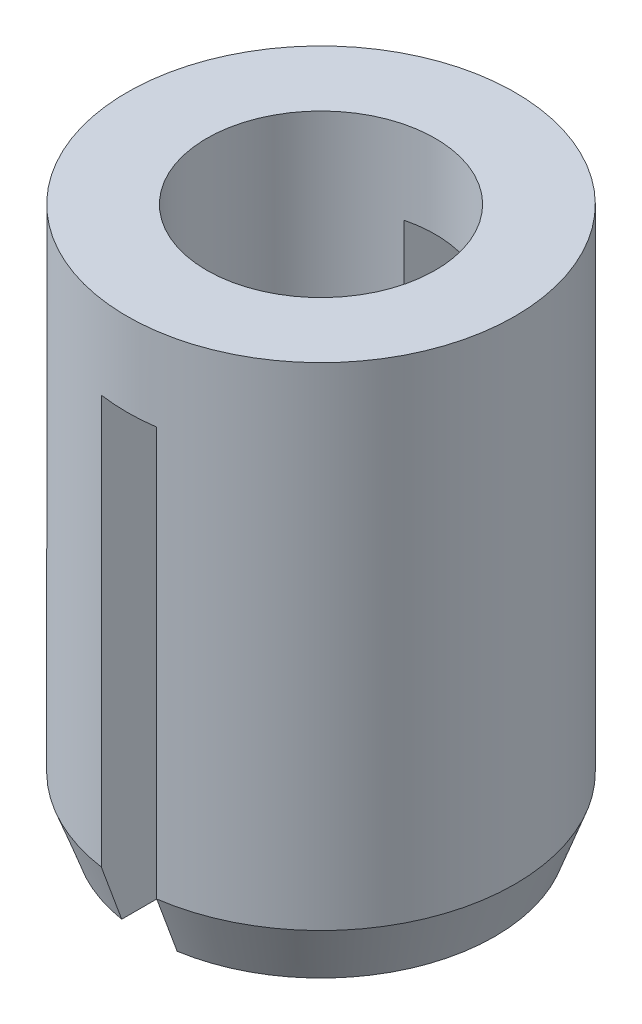
SolidWorks part; units mm, degrees
ref_plane "Front Plane" through (0, 0, 0) normal (0, 0, 1) x (1, 0, 0)
ref_plane "Top Plane" through (0, 0, 0) normal (0, 1, 0) x (1, 0, 0)
ref_plane "Right Plane" through (0, 0, 0) normal (1, 0, 0) x (0, 0, -1)
sketch "Sketch1" plane through (0, 0, 0) normal (0, 0, 1) x (1, 0, 0)
  line L0 (0, -7.9) -> (0, 0)
  line L1 (0, 0) -> (-2.8, 0)
  line L2 (-2.8, 0) -> (-2.8, -7.1)
  line L3 (-2.8, -7.1) -> (-2.5088, -7.9)
  line L4 (-2.5088, -7.9) -> (0, -7.9)
  line L5 (0, -7.9) -> (0, -6.7522) construction
  dimension "D1" = 7.9
  dimension "D2" = 5.6
  dimension "D3" = 0.8
  dimension "D4" = 20
revolve "Revolve1" add sketch "Sketch1" angle 360 about L5
hole_wizard "M4 Tapped Hole1" positions "Sketch3" profile "Sketch5" tap size "M4" standard "ISO" end condition through all
sketch "Sketch3" plane through (0, 0, 0) normal (0, 1, 0) x (1, 0, 0)
  point P0 (0, 0)
sketch "Sketch5" plane through (0, 0, 0) normal (1, 0, 0) x (0, 0, 1)
  line L0 (0, 0) -> (0, 7.9)
  line L1 (0, 7.9) -> (1.65, 7.9)
  line L2 (1.65, 7.9) -> (1.65, 0)
  line L5 (1.65, 0) -> (0, 0)
  line L11 (0, -6.35) -> (0, 107.95) construction
  dimension "Thru Tap Drill Dia." = 3.3
  dimension "Thru Tap Drill Depth" = 7.9
cosmetic thread "Hole Thread1" parameters "D2"=4
sketch "Sketch2" plane through (0, 0, 0) normal (0, 0, 1) x (1, 0, 0)
  line L0 (-1.65, -7.9) -> (1.65, -7.9) construction
  line L1 (0.4, -1.2) -> (-0.4, -1.2)
  line L2 (0.4, -1.2) -> (0.4, -7.9)
  line L3 (0.4, -7.9) -> (-0.4, -7.9)
  line L4 (-0.4, -1.2) -> (-0.4, -7.9)
  point P4 (0, -1.2)
  dimension "D1" = 0.8
  dimension "D2" = 1.2
extrude "Cut-Extrude1" cut sketch "Sketch2" against normal through all both and the other way through all
other "Freeze***"
